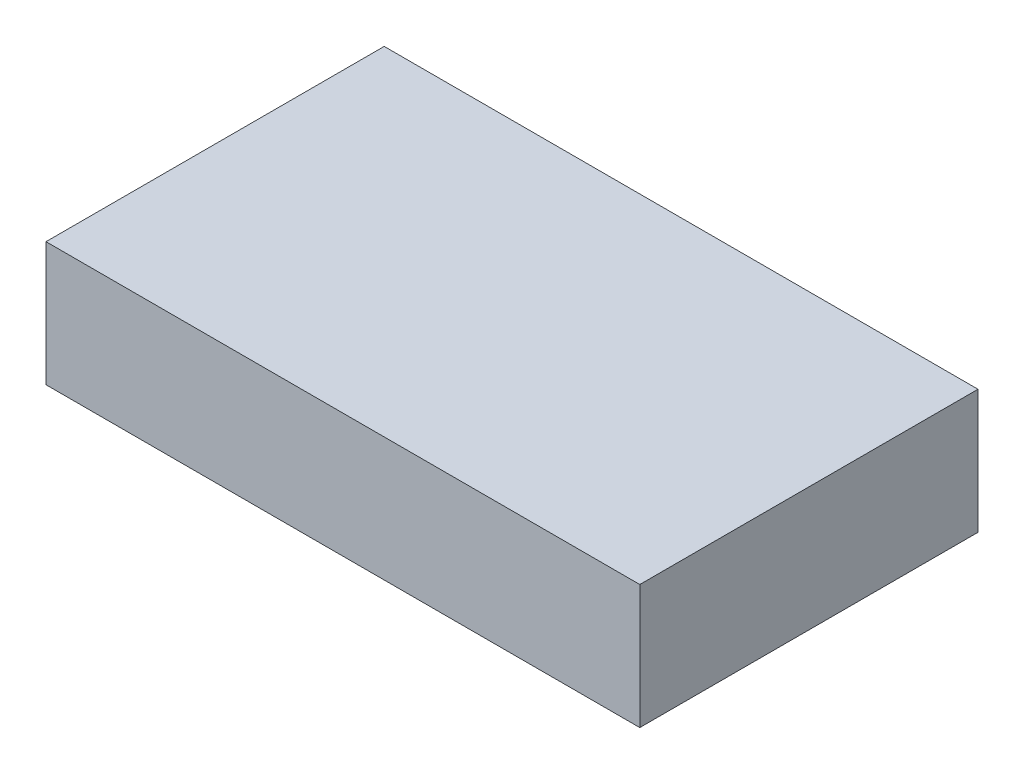
SolidWorks part; units mm, degrees
ref_plane "Alzado" through (0, 0, 0) normal (0, 0, 1) x (1, 0, 0)
ref_plane "Planta" through (0, 0, 0) normal (0, 1, 0) x (1, 0, 0)
ref_plane "Vista lateral" through (0, 0, 0) normal (1, 0, 0) x (0, 0, -1)
sketch "Croquis2" plane through (0, 0, 0) normal (0, 1, 0) x (1, 0, 0)
  line L1 (-57.5, -32.75) -> (57.5, -32.75)
  line L2 (-57.5, -32.75) -> (-57.5, 32.75)
  line L3 (-57.5, 32.75) -> (57.5, 32.75)
  line L4 (57.5, -32.75) -> (57.5, 32.75)
  line L5 (-57.5, -32.75) -> (57.5, 32.75) construction
  line L6 (-57.5, 32.75) -> (57.5, -32.75) construction
  point P0 (0, 0)
  dimension "D1" = 65.5
  dimension "D2" = 115
extrude "Saliente-Extruir1" add sketch "Croquis2" along normal blind 24
